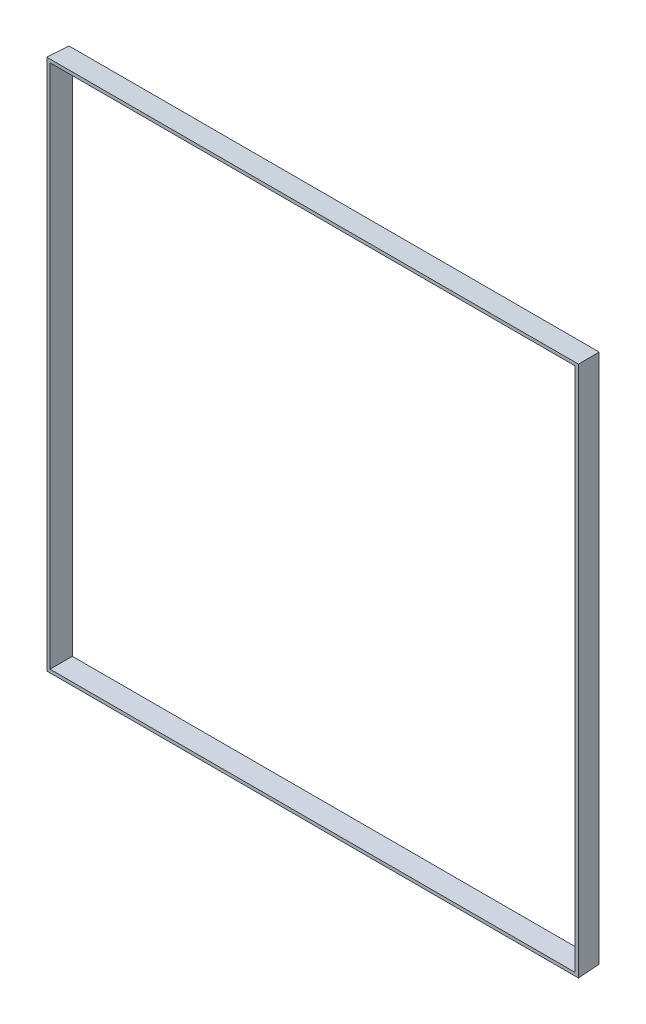
SolidWorks part; units mm, degrees
material "Rubber"
ref_plane "Front Plane" through (0, 0, 0) normal (0, 0, 1) x (1, 0, 0)
ref_plane "Top Plane" through (0, 0, 0) normal (0, 1, 0) x (1, 0, 0)
ref_plane "Right Plane" through (0, 0, 0) normal (1, 0, 0) x (0, 0, -1)
sketch "Sketch2" plane through (0, 0, 0) normal (0, 0, 1) x (1, 0, 0)
  line L1 (-123.3, -123.3) -> (123.3, -123.3)
  line L2 (-123.3, -123.3) -> (-123.3, 123.3)
  line L3 (-123.3, 123.3) -> (123.3, 123.3)
  line L4 (123.3, -123.3) -> (123.3, 123.3)
  line L5 (-123.3, -123.3) -> (123.3, 123.3) construction
  line L6 (-123.3, 123.3) -> (123.3, -123.3) construction
  point P0 (0, 0)
  dimension "D1" = 246.6
  dimension "D2" = 246.6
extrude "Boss-Extrude1" add sketch "Sketch2" against normal blind 10 draft 2
sketch "Sketch3" plane through (0, 0, 0) normal (0, 0, 1) x (1, 0, 0)
  line L0 (123.3, 123.3) -> (-123.3, 123.3) construction
  line L1 (-121.8, -121.8) -> (121.8, -121.8)
  line L2 (-121.8, -121.8) -> (-121.8, 121.8)
  line L3 (-121.8, 121.8) -> (121.8, 121.8)
  line L4 (121.8, -121.8) -> (121.8, 121.8)
  line L5 (-121.8, -121.8) -> (121.8, 121.8) construction
  line L6 (-121.8, 121.8) -> (121.8, -121.8) construction
  line L7 (-123.3, 123.3) -> (-123.3, -123.3) construction
  point P0 (0, 0)
  dimension "D1" = 1.5
  dimension "D2" = 1.5
extrude "Cut-Extrude1" cut sketch "Sketch3" against normal through all both draft 2 and the other way through all
